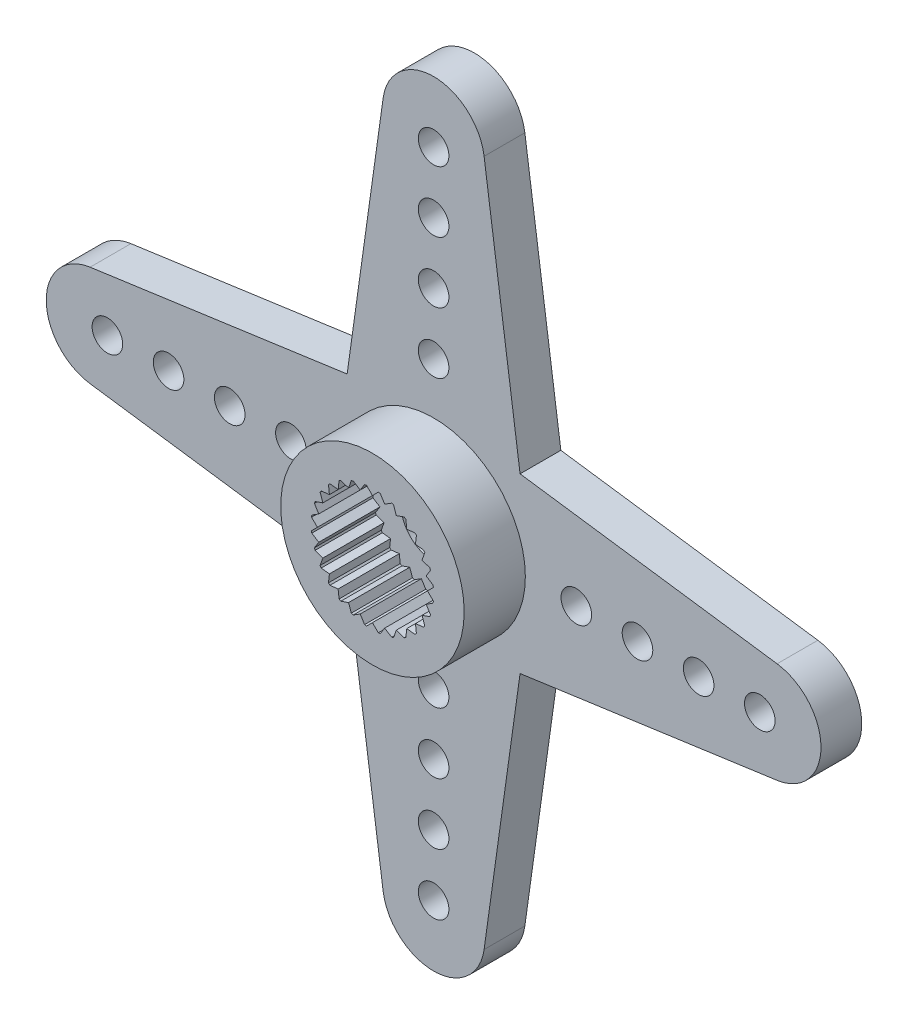
SolidWorks part; units mm, degrees
ref_plane "Plan de face" through (0, 0, 0) normal (0, 0, 1) x (1, 0, 0)
ref_plane "Plan de dessus" through (0, 0, 0) normal (0, 1, 0) x (1, 0, 0)
ref_plane "Plan de droite" through (0, 0, 0) normal (1, 0, 0) x (0, 0, -1)
sketch "Esquisse1" plane through (0, 0, 0) normal (0, 0, 1) x (1, 0, 0)
  circle A0 centre (0, 0) radius 5.75
  circle A1 centre (0, 0) radius 1.6
  dimension "D1" = 11.5
  dimension "D2" = 3.2
extrude "Boss.-Extru.1" add sketch "Esquisse1" along normal blind 5
sketch "Esquisse2" plane through (0, 0, 5) normal (0, 0, 1) x (1, 0, 0)
  circle A0 centre (0, 0) radius 3
  dimension "D1" = 6
extrude "Enlèv. mat.-Extru.1" cut sketch "Esquisse2" against normal blind 3
sketch "Esquisse3" plane through (0, 0, 5) normal (0, 0, 1) x (1, 0, 0)
  circle A0 centre (0, 0) radius 5.75
  circle A1 centre (0, 0) radius 4.5
  circle A2 centre (0, 0) radius 3 construction
  circle A3 centre (0, 0) radius 5.75 construction
  dimension "D1" = 1.5
extrude "Enlèv. mat.-Extru.2" cut sketch "Esquisse3" against normal blind 3
sketch "Esquisse4" plane through (0, 0, 0) normal (0, 0, -1) x (-1, 0, 0)
  line L0 (-4.3, 3.8174) -> (-2.4759, 16.8466)
  line L1 (2.4759, 16.8466) -> (4.3, 3.8174)
  line L2 (-5.2729, 19) -> (6.8365, 19) construction
  line L3 (0, 0) -> (0, 24.2526) construction
  circle A0 centre (0, 0) radius 5.75 construction
  arc A1 (-2.4759, 16.8466) -> (2.4759, 16.8466) centre (0, 16.5) cw
  arc A2 (-4.3, 3.8174) -> (4.3, 3.8174) centre (0, 0) cw
  dimension "D2" = 2.5
  dimension "D1" = 8.6
  dimension "D3" = 19
extrude "Boss.-Extru.2" add sketch "Esquisse4" against normal up to surface (2 mm away) up to face at (4.5, 0, 2)
pattern_circular "Répétition circulaire1" count 4 every 90 about axis through (0, 0, 0) along (0, 0, 1) of "Boss.-Extru.2"
sketch "Esquisse5" plane through (0, 0, 0) normal (0, 0, -1) x (-1, 0, 0)
  line L0 (0, 0) -> (0, 20.4605) construction
  circle A0 centre (0, 7) radius 0.75
  circle A1 centre (0, 10) radius 0.75
  circle A2 centre (0, 13) radius 0.75
  circle A3 centre (0, 16) radius 0.75
  dimension "D5" = 1.5
  dimension "D6" = 1.5
  dimension "D7" = 1.5
  dimension "D8" = 1.5
  dimension "D1" = 7
  dimension "D2" = 3
  dimension "D3" = 3
  dimension "D4" = 3
extrude "Enlèv. mat.-Extru.3" cut sketch "Esquisse5" against normal blind 3
pattern_circular "Répétition circulaire2" count 4 over 360 about axis through (0, 0, 0) along (0, 0, 1) of "Enlèv. mat.-Extru.3"
sketch "Esquisse6" plane through (0, 0, 5) normal (0, 0, 1) x (1, 0, 0)
  line L0 (-1.598, 3) -> (1.8482, 3) construction
  line L1 (0, 0) -> (0, 5.9454) construction
  line L2 (-0.3, 3) -> (0, 2.7)
  line L3 (0, 2.7) -> (0.3, 3)
  line L4 (0.3, 3) -> (-0.3, 3)
  circle A0 centre (0, 0) radius 3 construction
  dimension "D1" = 0.3
  dimension "D2" = 0.6
extrude "Boss.-Extru.3" add sketch "Esquisse6" against normal up to surface (3 mm away) up to face at (1.6, 0, 2)
pattern_circular "Répétition circulaire3" count 28 over 360 about axis through (0, 0, 0) along (0, 0, 1) of "Boss.-Extru.3"
sketch "Esquisse7" plane through (0, 0, 0) normal (0, 0, -1) x (-1, 0, 0)
  circle A0 centre (0, 0) radius 1.6
  circle A1 centre (0, 0) radius 3
  circle A2 centre (0, 0) radius 1.6 construction
  dimension "D1" = 6
extrude "Enlèv. mat.-Extru.4" cut sketch "Esquisse7" against normal blind 1
sketch "Esquisse8" plane through (0, 0, 0) normal (0, 0, -1) x (-1, 0, 0)
  circle A0 centre (0, 0) radius 3.4
  circle A1 centre (0, 0) radius 4.7
  circle A2 centre (0, 0) radius 3 construction
  dimension "D1" = 0.4
  dimension "D2" = 1.3
extrude "Enlèv. mat.-Extru.5" cut sketch "Esquisse8" against normal blind 1
